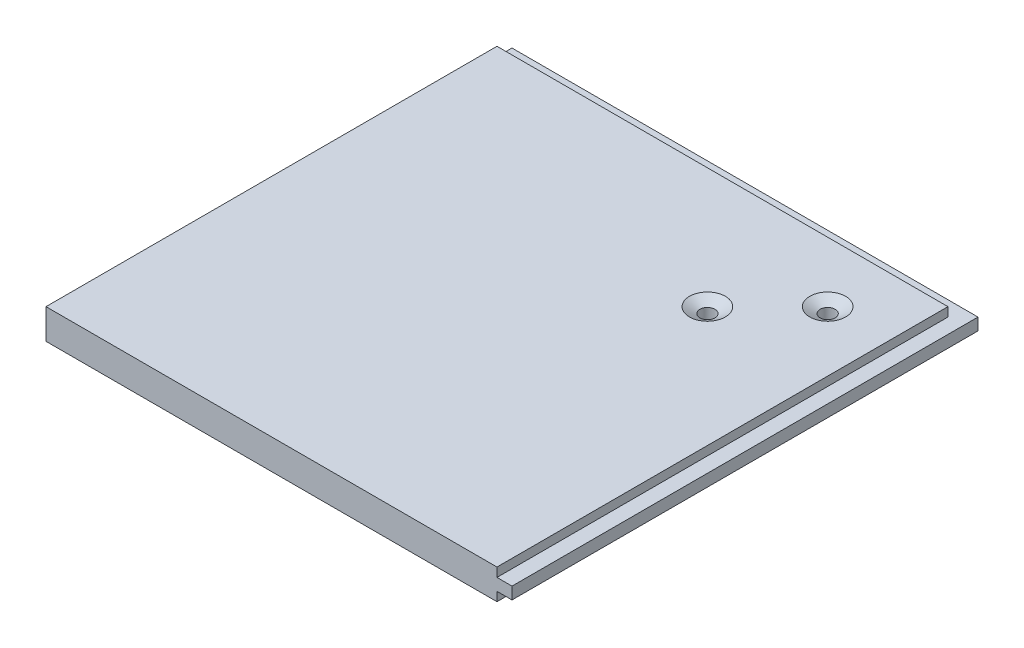
SolidWorks part; units mm, degrees
ref_plane "Front Plane" through (0, 0, 0) normal (0, 0, 1) x (1, 0, 0)
ref_plane "Top Plane" through (0, 0, 0) normal (0, 1, 0) x (1, 0, 0)
ref_plane "Right Plane" through (0, 0, 0) normal (1, 0, 0) x (0, 0, -1)
sketch "Sketch1" plane through (0, 0, 0) normal (0, 1, 0) x (1, 0, 0)
  line L0 (0, 0) -> (0, 150)
  line L1 (0, 0) -> (150, 0)
  line L2 (0, 150) -> (150, 150)
  line L3 (150, 150) -> (150, 0)
  dimension "D1" = 150
  dimension "D2" = 150
extrude "Boss-Extrude1" add sketch "Sketch1" along normal blind 10
sketch "Sketch2" plane through (150, 0, 0) normal (1, 0, 0) x (0, 0, -1)
  line L0 (0, 7) -> (150, 7)
  line L1 (0, 10) -> (0, 0) construction
  line L2 (150, 10) -> (150, 0) construction
  line L3 (150, 7) -> (150, 3)
  line L4 (150, 3) -> (0, 3)
  line L5 (0, 3) -> (0, 7)
  line L6 (0, 0) -> (150, 0) construction
  dimension "D1" = 4
  dimension "D2" = 3
extrude "Boss-Extrude2" add sketch "Sketch2" along normal blind 5
sketch "Sketch3" plane through (0, 0, -150) normal (0, 0, -1) x (-1, 0, 0)
  line L0 (0, 7) -> (-155, 7)
  line L1 (0, 10) -> (0, 0) construction
  line L2 (-155, 7) -> (-155, 3)
  line L3 (-155, 3) -> (0, 3)
  line L4 (0, 7) -> (0, 3)
  dimension "D1" = 4
extrude "Boss-Extrude3" add sketch "Sketch3" along normal blind 5
sketch "Sketch4" plane through (0, 10, 0) normal (0, 1, 0) x (1, 0, 0)
  line L0 (150, 150) -> (0, 150) construction
  line L1 (150, 0) -> (150, 150) construction
  line L2 (0, 150) -> (150, 150) construction
  circle A0 centre (130, 130) radius 2.5
  circle A1 centre (110, 110) radius 2.5
  dimension "D5" = 5
  dimension "D6" = 5
  dimension "D1" = 40
  dimension "D2" = 40
  dimension "D3" = 20
  dimension "D4" = 20
extrude "Cut-Extrude1" cut sketch "Sketch4" against normal through all both and the other way through all
chamfer "Chamfer1" distance 2 angle 60 2 edges at (130, 10, -132.5) (110, 10, -112.5)
